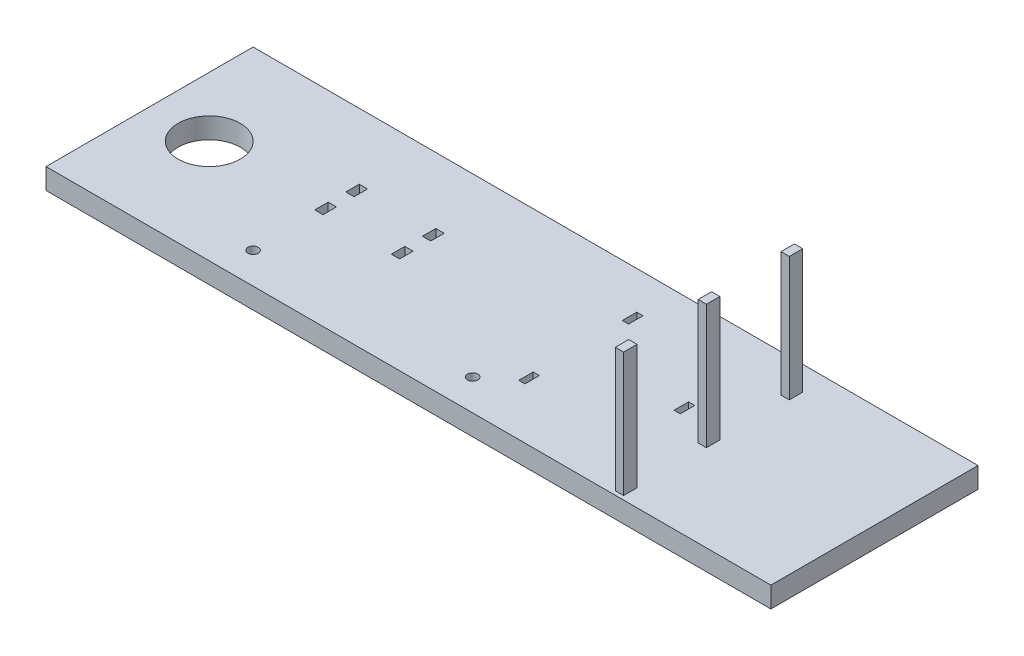
SolidWorks part; units mm, degrees
ref_plane "Front Plane" through (0, 0, 0) normal (0, 0, 1) x (1, 0, 0)
ref_plane "Top Plane" through (0, 0, 0) normal (0, 1, 0) x (1, 0, 0)
ref_plane "Right Plane" through (0, 0, 0) normal (1, 0, 0) x (0, 0, -1)
sketch "Sketch1" plane through (0, 0, 0) normal (0, 1, 0) x (1, 0, 0)
  line L1 (-17.5, -5) -> (17.5, -5)
  line L2 (-17.5, -5) -> (-17.5, 5)
  line L3 (-17.5, 5) -> (17.5, 5)
  line L4 (17.5, -5) -> (17.5, 5)
  line L5 (-17.5, -5) -> (17.5, 5) construction
  line L6 (-17.5, 5) -> (17.5, -5) construction
  point P0 (0, 0)
  dimension "D1" = 10
  dimension "D2" = 35
extrude "Boss-Extrude1" add sketch "Sketch1" along normal blind 1
sketch "Sketch2" plane through (0, 0, 0) normal (0, -1, 0) x (1, 0, 0)
  line L0 (-17.5, 0) -> (17.5, 0) construction
  line L1 (-9.2, -0.325) -> (-8.8, -0.325)
  line L2 (-9.2, -0.325) -> (-9.2, 0.325)
  line L3 (-9.2, 0.325) -> (-8.8, 0.325)
  line L4 (-8.8, -0.325) -> (-8.8, 0.325)
  line L5 (-9.2, -0.325) -> (-8.8, 0.325) construction
  line L6 (-9.2, 0.325) -> (-8.8, -0.325) construction
  line L7 (-9.2, -1.825) -> (-8.8, -1.825)
  line L8 (-9.2, -1.825) -> (-9.2, -1.175)
  line L9 (-9.2, -1.175) -> (-8.8, -1.175)
  line L10 (-8.8, -1.825) -> (-8.8, -1.175)
  line L11 (-9.2, -1.825) -> (-8.8, -1.175) construction
  line L12 (-9.2, -1.175) -> (-8.8, -1.825) construction
  line L13 (-17.5, -5) -> (-17.5, 5) construction
  line L14 (17.5, 5) -> (17.5, -5) construction
  line L15 (-5.5, 0.325) -> (-5.1, 0.325)
  line L16 (-5.5, -0.325) -> (-5.5, 0.325)
  line L17 (-5.5, -0.325) -> (-5.1, -0.325)
  line L18 (-5.1, -0.325) -> (-5.1, 0.325)
  line L19 (-5.5, -1.175) -> (-5.1, -1.175)
  line L20 (-5.5, -1.825) -> (-5.5, -1.175)
  line L21 (-5.5, -1.825) -> (-5.1, -1.825)
  line L22 (-5.1, -1.825) -> (-5.1, -1.175)
  line L24 (7.85, -0.675) -> (8.15, -0.675)
  line L25 (7.85, -0.675) -> (7.85, 0.025)
  line L26 (7.85, 0.025) -> (8.15, 0.025)
  line L27 (8.15, -0.675) -> (8.15, 0.025)
  line L28 (7.85, -0.675) -> (8.15, 0.025) construction
  line L29 (7.85, 0.025) -> (8.15, -0.675) construction
  line L30 (2.85, 1.825) -> (3.15, 1.825)
  line L31 (2.85, 1.825) -> (2.85, 2.525)
  line L32 (2.85, 2.525) -> (3.15, 2.525)
  line L33 (3.15, 1.825) -> (3.15, 2.525)
  line L34 (2.85, 1.825) -> (3.15, 2.525) construction
  line L35 (2.85, 2.525) -> (3.15, 1.825) construction
  line L36 (2.85, -2.475) -> (3.15, -2.475)
  line L37 (2.85, -2.475) -> (2.85, -3.175)
  line L38 (2.85, -3.175) -> (3.15, -3.175)
  line L39 (3.15, -2.475) -> (3.15, -3.175)
  line L40 (2.85, -2.475) -> (3.15, -3.175) construction
  line L41 (2.85, -3.175) -> (3.15, -2.475) construction
  circle A0 centre (-9, 3.5) radius 0.25
  circle A1 centre (1.6, 3.5) radius 0.25
  circle A2 centre (-14.62, 0) radius 1.5
  point P0 (-9, 0)
  point P5 (-9, -1.5)
  point P16 (-5.3, -1.5)
  point P19 (-5.3, 0)
  point P32 (8, -0.325)
  point P37 (3, 2.175)
  point P42 (3, -2.825)
  dimension "D11" = 3.5
  dimension "D12" = 0.5
  dimension "D1" = 0.4
  dimension "D2" = 0.65
  dimension "D3" = 0.65
  dimension "D4" = 0.4
  dimension "D5" = 0
  dimension "D6" = 1.5
  dimension "D7" = 9
  dimension "D8" = 9
  dimension "D13" = 10.6
  dimension "D14" = 3.5
  dimension "D15" = 0.7
  dimension "D16" = 0.3
  dimension "D17" = 0.7
  dimension "D18" = 0.3
  dimension "D19" = 0.7
  dimension "D20" = 0.3
  dimension "D21" = 2.5
  dimension "D22" = 5
  dimension "D23" = 2.5
  dimension "D24" = 5
  dimension "D25" = 3
  dimension "D26" = 0
  dimension "D9" = 2
  dimension "D10" = 2
extrude "Cut-Extrude1" cut sketch "Sketch2" against normal blind 1
sketch "Sketch3" plane through (0, 1, 0) normal (0, 1, 0) x (1, 0, 0)
  line L0 (9.8, -0.1626) -> (10.2, -0.1626)
  line L1 (9.8, 3.8374) -> (10.2, 3.8374)
  line L2 (9.8, 3.8374) -> (9.8, 3.1874)
  line L3 (9.8, 3.1874) -> (10.2, 3.1874)
  line L4 (10.2, 3.8374) -> (10.2, 3.1874)
  line L5 (9.8, 3.8374) -> (10.2, 3.1874) construction
  line L6 (9.8, 3.1874) -> (10.2, 3.8374) construction
  line L7 (9.8, -0.1626) -> (9.8, -0.8126)
  line L8 (9.8, -0.8126) -> (10.2, -0.8126)
  line L9 (10.2, -0.1626) -> (10.2, -0.8126)
  line L10 (9.8, -4.1626) -> (10.2, -4.1626)
  line L11 (9.8, -4.1626) -> (9.8, -4.8126)
  line L12 (9.8, -4.8126) -> (10.2, -4.8126)
  line L13 (10.2, -4.1626) -> (10.2, -4.8126)
  point P0 (10, 3.5124)
  point P8 (10, -0.4876)
  point P13 (10, -4.4876)
  dimension "D1" = 0.4
  dimension "D2" = 0.65
  dimension "D3" = 10
  dimension "D4" = 3
extrude "Boss-Extrude2" add sketch "Sketch3" along normal blind 6
